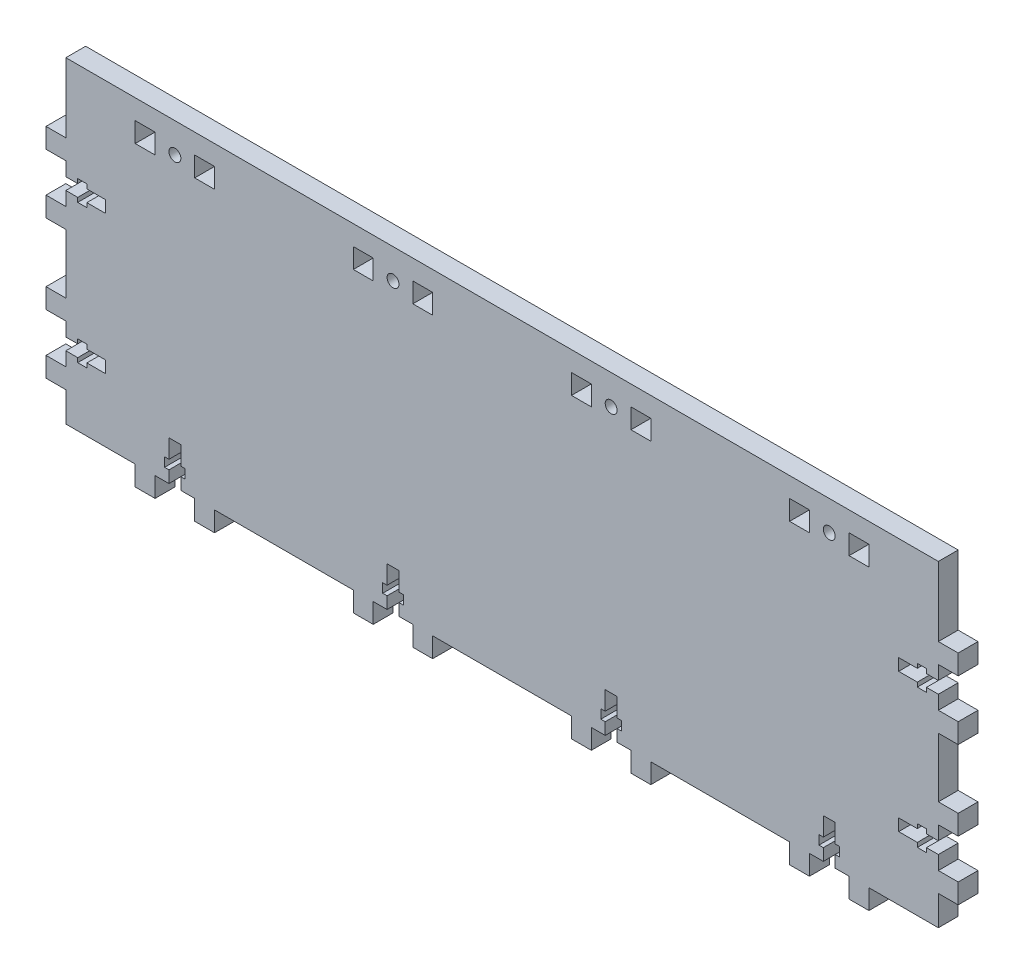
SolidWorks part; units mm, degrees
ref_plane "Front Plane" through (0, 0, 0) normal (0, 0, 1) x (1, 0, 0)
ref_plane "Top Plane" through (0, 0, 0) normal (0, 1, 0) x (1, 0, 0)
ref_plane "Right Plane" through (0, 0, 0) normal (1, 0, 0) x (0, 0, -1)
sketch "Sketch1" plane through (0, 0, 0) normal (0, 0, 1) x (1, 0, 0)
  line L0 (0, 35) -> (110, 35) construction
  line L1 (-110, 70) -> (110, 70) construction
  line L2 (-110, 70) -> (-110, 0)
  line L3 (-110, 0) -> (110, 0)
  line L4 (110, 70) -> (110, 0)
  line L5 (-110, 70) -> (110, 0) construction
  line L6 (-110, 0) -> (110, 70) construction
  line L7 (0, 35) -> (0, 0) construction
  line L8 (-110, 70) -> (-110, 80)
  line L9 (-110, 80) -> (110, 80)
  line L10 (110, 80) -> (110, 70)
  point P0 (0, 35)
  point P9 (-88.4525, 74.6606)
  point P11 (36.2055, 76.021)
  point P12 (-39.2705, 76.0821)
  point P13 (86.1856, 97.4711)
  point P14 (29.641, 76.1442)
  point P16 (166.6985, 58.3506)
  point P17 (0, 0)
  point P18 (0, 0)
  line B0 (24.9, 3) -> (24.9, 5.3)
  line B1 (29, 5.3) -> (29, 10)
  line B2 (26, 10) -> (26, 5.3)
  line B3 (24.9, 5.3) -> (26, 5.3)
  line B4 (27.5, 0) -> (27.5, 11.2208) construction
  line B5 (26, 0) -> (22.5, 0)
  line B6 (22.5, -5) -> (17.5, -5)
  line B7 (17.5, -5) -> (17.5, 0)
  line B8 (22.5, -5) -> (22.5, 0)
  line B9 (29, 0) -> (32.5, 0)
  line B10 (32.5, 0) -> (32.5, -5)
  line B11 (32.5, -5) -> (37.5, -5)
  line B12 (37.5, -5) -> (37.5, 0)
  line B13 (29, 10) -> (26, 10)
  line B14 (29, 0) -> (29, 3)
  line B15 (26, 3) -> (26, 0)
  line B16 (26, 0) -> (29, 0) construction
  line B17 (29, 5.3) -> (30.1, 5.3)
  line B18 (30.1, 3) -> (29, 3)
  line B19 (26, 3) -> (24.9, 3)
  line B20 (30.1, 5.3) -> (30.1, 3)
  line B21 (27.5, 10) -> (27.5, 0) construction
  line B22 (79.9, 3) -> (79.9, 5.3)
  line B23 (84, 5.3) -> (84, 10)
  line B24 (81, 10) -> (81, 5.3)
  line B25 (79.9, 5.3) -> (81, 5.3)
  line B26 (82.5, 0) -> (82.5, 11.2208) construction
  line B27 (81, 0) -> (77.5, 0)
  line B28 (77.5, -5) -> (72.5, -5)
  line B29 (72.5, -5) -> (72.5, 0)
  line B30 (77.5, -5) -> (77.5, 0)
  line B31 (84, 0) -> (87.5, 0)
  line B32 (87.5, 0) -> (87.5, -5)
  line B33 (87.5, -5) -> (92.5, -5)
  line B34 (92.5, -5) -> (92.5, 0)
  line B35 (84, 10) -> (81, 10)
  line B36 (84, 0) -> (84, 3)
  line B37 (81, 3) -> (81, 0)
  line B38 (81, 0) -> (84, 0) construction
  line B39 (84, 5.3) -> (85.1, 5.3)
  line B40 (85.1, 3) -> (84, 3)
  line B41 (81, 3) -> (79.9, 3)
  line B42 (85.1, 5.3) -> (85.1, 3)
  line B43 (82.5, 10) -> (82.5, 0) construction
  line B44 (-79.9, 3) -> (-79.9, 5.3)
  line B45 (-84, 5.3) -> (-84, 10)
  line B46 (-81, 10) -> (-81, 5.3)
  line B47 (-79.9, 5.3) -> (-81, 5.3)
  line B48 (-82.5, 0) -> (-82.5, 11.2208) construction
  line B49 (-81, 0) -> (-77.5, 0)
  line B50 (-77.5, -5) -> (-72.5, -5)
  line B51 (-72.5, -5) -> (-72.5, 0)
  line B52 (-77.5, -5) -> (-77.5, 0)
  line B53 (-84, 0) -> (-87.5, 0)
  line B54 (-87.5, 0) -> (-87.5, -5)
  line B55 (-87.5, -5) -> (-92.5, -5)
  line B56 (-92.5, -5) -> (-92.5, 0)
  line B57 (-84, 10) -> (-81, 10)
  line B58 (-84, 0) -> (-84, 3)
  line B59 (-81, 3) -> (-81, 0)
  line B60 (-81, 0) -> (-84, 0) construction
  line B61 (-84, 5.3) -> (-85.1, 5.3)
  line B62 (-85.1, 3) -> (-84, 3)
  line B63 (-81, 3) -> (-79.9, 3)
  line B64 (-85.1, 5.3) -> (-85.1, 3)
  line B65 (-82.5, 10) -> (-82.5, 0) construction
  line B66 (-24.9, 3) -> (-24.9, 5.3)
  line B67 (-29, 5.3) -> (-29, 10)
  line B68 (-26, 10) -> (-26, 5.3)
  line B69 (-24.9, 5.3) -> (-26, 5.3)
  line B70 (-27.5, 0) -> (-27.5, 11.2208) construction
  line B71 (-26, 0) -> (-22.5, 0)
  line B72 (-22.5, -5) -> (-17.5, -5)
  line B73 (-17.5, -5) -> (-17.5, 0)
  line B74 (-22.5, -5) -> (-22.5, 0)
  line B75 (-29, 0) -> (-32.5, 0)
  line B76 (-32.5, 0) -> (-32.5, -5)
  line B77 (-32.5, -5) -> (-37.5, -5)
  line B78 (-37.5, -5) -> (-37.5, 0)
  line B79 (-29, 10) -> (-26, 10)
  line B80 (-29, 0) -> (-29, 3)
  line B81 (-26, 3) -> (-26, 0)
  line B82 (-26, 0) -> (-29, 0) construction
  line B83 (-29, 5.3) -> (-30.1, 5.3)
  line B84 (-30.1, 3) -> (-29, 3)
  line B85 (-26, 3) -> (-24.9, 3)
  line B86 (-30.1, 5.3) -> (-30.1, 3)
  line B87 (-27.5, 10) -> (-27.5, 0) construction
  line B88 (-87.5, 72.5) -> (-77.5, 72.5) construction
  line B89 (-87.5, 70) -> (-92.5, 70)
  line B90 (-87.5, 70) -> (-87.5, 75)
  line B91 (-87.5, 75) -> (-92.5, 75)
  line B92 (-92.5, 70) -> (-92.5, 75)
  line B93 (-77.5, 70) -> (-72.5, 70)
  line B94 (-77.5, 70) -> (-77.5, 75)
  line B95 (-77.5, 75) -> (-72.5, 75)
  line B96 (-72.5, 70) -> (-72.5, 75)
  line B97 (-82.5, 72.5) -> (-82.5, 65.5276) construction
  circle B98 centre (-82.5, 72.5) radius 1.5
  line B99 (22.5, 72.5) -> (32.5, 72.5) construction
  line B100 (22.5, 70) -> (17.5, 70)
  line B101 (22.5, 70) -> (22.5, 75)
  line B102 (22.5, 75) -> (17.5, 75)
  line B103 (17.5, 70) -> (17.5, 75)
  line B104 (32.5, 70) -> (37.5, 70)
  line B105 (32.5, 70) -> (32.5, 75)
  line B106 (32.5, 75) -> (37.5, 75)
  line B107 (37.5, 70) -> (37.5, 75)
  line B108 (27.5, 72.5) -> (27.5, 65.5276) construction
  circle B109 centre (27.5, 72.5) radius 1.5
  line B110 (-32.5, 72.5) -> (-22.5, 72.5) construction
  line B111 (-32.5, 70) -> (-37.5, 70)
  line B112 (-32.5, 70) -> (-32.5, 75)
  line B113 (-32.5, 75) -> (-37.5, 75)
  line B114 (-37.5, 70) -> (-37.5, 75)
  line B115 (-22.5, 70) -> (-17.5, 70)
  line B116 (-22.5, 70) -> (-22.5, 75)
  line B117 (-22.5, 75) -> (-17.5, 75)
  line B118 (-17.5, 70) -> (-17.5, 75)
  line B119 (-27.5, 72.5) -> (-27.5, 65.5276) construction
  circle B120 centre (-27.5, 72.5) radius 1.5
  line B121 (77.5, 72.5) -> (87.5, 72.5) construction
  line B122 (77.5, 70) -> (72.5, 70)
  line B123 (77.5, 70) -> (77.5, 75)
  line B124 (77.5, 75) -> (72.5, 75)
  line B125 (72.5, 70) -> (72.5, 75)
  line B126 (87.5, 70) -> (92.5, 70)
  line B127 (87.5, 70) -> (87.5, 75)
  line B128 (87.5, 75) -> (92.5, 75)
  line B129 (92.5, 70) -> (92.5, 75)
  line B130 (82.5, 72.5) -> (82.5, 65.5276) construction
  circle B131 centre (82.5, 72.5) radius 1.5
  line B132 (107, 49.9) -> (104.7, 49.9)
  line B133 (104.7, 54) -> (100, 54)
  line B134 (100, 51) -> (104.7, 51)
  line B135 (104.7, 49.9) -> (104.7, 51)
  line B136 (110, 52.5) -> (98.7792, 52.5) construction
  line B137 (110, 51) -> (110, 47.5)
  line B138 (115, 47.5) -> (115, 42.5)
  line B139 (115, 42.5) -> (110, 42.5)
  line B140 (115, 47.5) -> (110, 47.5)
  line B141 (110, 54) -> (110, 57.5)
  line B142 (110, 57.5) -> (115, 57.5)
  line B143 (115, 57.5) -> (115, 62.5)
  line B144 (115, 62.5) -> (110, 62.5)
  line B145 (100, 54) -> (100, 51)
  line B146 (110, 54) -> (107, 54)
  line B147 (107, 51) -> (110, 51)
  line B148 (110, 51) -> (110, 54) construction
  line B149 (104.7, 54) -> (104.7, 55.1)
  line B150 (107, 55.1) -> (107, 54)
  line B151 (107, 51) -> (107, 49.9)
  line B152 (104.7, 55.1) -> (107, 55.1)
  line B153 (100, 52.5) -> (110, 52.5) construction
  line B154 (107, 20.1) -> (104.7, 20.1)
  line B155 (104.7, 16) -> (100, 16)
  line B156 (100, 19) -> (104.7, 19)
  line B157 (104.7, 20.1) -> (104.7, 19)
  line B158 (110, 17.5) -> (98.7792, 17.5) construction
  line B159 (110, 19) -> (110, 22.5)
  line B160 (115, 22.5) -> (115, 27.5)
  line B161 (115, 27.5) -> (110, 27.5)
  line B162 (115, 22.5) -> (110, 22.5)
  line B163 (110, 16) -> (110, 12.5)
  line B164 (110, 12.5) -> (115, 12.5)
  line B165 (115, 12.5) -> (115, 7.5)
  line B166 (115, 7.5) -> (110, 7.5)
  line B167 (100, 16) -> (100, 19)
  line B168 (110, 16) -> (107, 16)
  line B169 (107, 19) -> (110, 19)
  line B170 (110, 19) -> (110, 16) construction
  line B171 (104.7, 16) -> (104.7, 14.9)
  line B172 (107, 14.9) -> (107, 16)
  line B173 (107, 19) -> (107, 20.1)
  line B174 (104.7, 14.9) -> (107, 14.9)
  line B175 (100, 17.5) -> (110, 17.5) construction
  line B176 (-107, 20.1) -> (-104.7, 20.1)
  line B177 (-104.7, 16) -> (-100, 16)
  line B178 (-100, 19) -> (-104.7, 19)
  line B179 (-104.7, 20.1) -> (-104.7, 19)
  line B180 (-110, 17.5) -> (-98.7792, 17.5) construction
  line B181 (-110, 19) -> (-110, 22.5)
  line B182 (-115, 22.5) -> (-115, 27.5)
  line B183 (-115, 27.5) -> (-110, 27.5)
  line B184 (-115, 22.5) -> (-110, 22.5)
  line B185 (-110, 16) -> (-110, 12.5)
  line B186 (-110, 12.5) -> (-115, 12.5)
  line B187 (-115, 12.5) -> (-115, 7.5)
  line B188 (-115, 7.5) -> (-110, 7.5)
  line B189 (-100, 16) -> (-100, 19)
  line B190 (-110, 16) -> (-107, 16)
  line B191 (-107, 19) -> (-110, 19)
  line B192 (-110, 19) -> (-110, 16) construction
  line B193 (-104.7, 16) -> (-104.7, 14.9)
  line B194 (-107, 14.9) -> (-107, 16)
  line B195 (-107, 19) -> (-107, 20.1)
  line B196 (-104.7, 14.9) -> (-107, 14.9)
  line B197 (-100, 17.5) -> (-110, 17.5) construction
  line B198 (-107, 49.9) -> (-104.7, 49.9)
  line B199 (-104.7, 54) -> (-100, 54)
  line B200 (-100, 51) -> (-104.7, 51)
  line B201 (-104.7, 49.9) -> (-104.7, 51)
  line B202 (-110, 52.5) -> (-98.7792, 52.5) construction
  line B203 (-110, 51) -> (-110, 47.5)
  line B204 (-115, 47.5) -> (-115, 42.5)
  line B205 (-115, 42.5) -> (-110, 42.5)
  line B206 (-115, 47.5) -> (-110, 47.5)
  line B207 (-110, 54) -> (-110, 57.5)
  line B208 (-110, 57.5) -> (-115, 57.5)
  line B209 (-115, 57.5) -> (-115, 62.5)
  line B210 (-115, 62.5) -> (-110, 62.5)
  line B211 (-100, 54) -> (-100, 51)
  line B212 (-110, 54) -> (-107, 54)
  line B213 (-107, 51) -> (-110, 51)
  line B214 (-110, 51) -> (-110, 54) construction
  line B215 (-104.7, 54) -> (-104.7, 55.1)
  line B216 (-107, 55.1) -> (-107, 54)
  line B217 (-107, 51) -> (-107, 49.9)
  line B218 (-104.7, 55.1) -> (-107, 55.1)
  line B219 (-100, 52.5) -> (-110, 52.5) construction
  dimension "D1" = 70
  dimension "D2" = 220
  dimension "D3" = 27.5
  dimension "D4" = 82.5
  dimension "D5" = 10
sketch_block_instance "Insert M3 plots ep 5mm-1"
sketch_block "Insert M3 plots ep 5mm" parameters "D1"=10, "D2"=5, "D3"=5
sketch_block_instance "Decoupe Insert M3-4"
sketch_block "Decoupe Insert M3" parameters "D1"=5.2, "D2"=3, "D3"=2.3, "D4"=3, "D5"=10
sketch_block_instance "Insert M3 plots ep 5mm-2"
sketch_block_instance "Insert M3 plots ep 5mm-3"
sketch_block_instance "Insert M3 plots ep 5mm-4"
sketch_block_instance "Trou M3 plots 5mm-22"
sketch_block "Trou M3 plots 5mm" parameters "D2"=3, "D1"=5, "D3"=5, "D4"=10
sketch_block_instance "Trou M3 plots 5mm-23"
sketch_block_instance "Trou M3 plots 5mm-24"
sketch_block_instance "Trou M3 plots 5mm-25"
sketch_block_instance "Insert M3 plots ep 5mm-5"
sketch_block_instance "Insert M3 plots ep 5mm-6"
sketch_block_instance "Insert M3 plots ep 5mm-7"
sketch_block_instance "Insert M3 plots ep 5mm-8"
extrude "Boss-Extrude2" add sketch "Sketch1" along normal blind 5 contours B143 B144 L4 B142 | B138 B140 L4 B139 | B162 B160 B161 L4 | B166 B165 B164 L4 | B217 B213 L2 B191 B195 B176 B179 B178 B189 B177 B193 B196 B194 B190 L3 B58 B62 B64 B61 B45 B57 B46 B47 B44 B63 B59 B80 B84 B86 B83 B67 B79 B68 B69 B66 B85 B81 | B33 B34 L3 B32 | B28 B30 L3 B29 | B11 B12 L3 B10 | B6 B8 L3 B7 | B74 B72 B73 L3 | B78 B77 B76 L3 | B210 B209 B208 L2 | B206 B204 B205 L2 | B182 B184 L2 B183 | B187 B188 L2 B186 | B56 B55 B54 L3 | B52 B50 B51 L3
